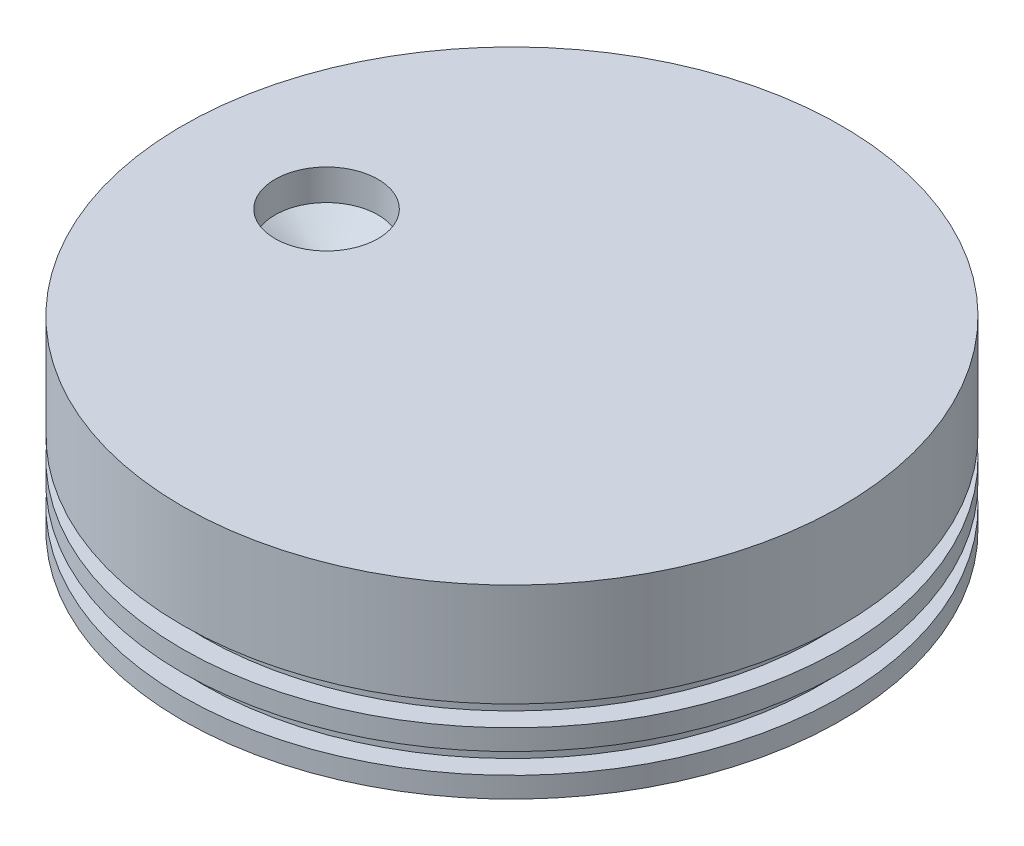
SolidWorks part; units mm, degrees
ref_plane "Front Plane" through (0, 0, 0) normal (0, 0, 1) x (1, 0, 0)
ref_plane "Top Plane" through (0, 0, 0) normal (0, 1, 0) x (1, 0, 0)
ref_plane "Right Plane" through (0, 0, 0) normal (1, 0, 0) x (0, 0, -1)
sketch "Sketch2" plane through (0, 0, 0) normal (0, 0, 1) x (1, 0, 0)
  line L0 (20.32, 0) -> (20.32, -11.43)
  line L1 (20.32, -11.43) -> (0, -11.43)
  line L2 (0, -11.43) -> (0, -10.16)
  line L3 (0, 0) -> (20.32, 0)
  line L4 (20.32, 0) -> (20.32, -34.3325) construction
  line L5 (0, -10.16) -> (1.27, -10.16)
  line L6 (1.27, -10.16) -> (1.27, -8.89)
  line L7 (1.27, -8.89) -> (0, -8.89)
  line L8 (0, -8.89) -> (0, -7.62)
  line L9 (0, -7.62) -> (1.27, -7.62)
  line L10 (1.27, -7.62) -> (1.27, -6.35)
  line L11 (1.27, -6.35) -> (0, -6.35)
  line L12 (0, -6.35) -> (0, 0)
  dimension "D1" = 20.32
  dimension "D2" = 1.27
  dimension "D3" = 1.27
  dimension "D4" = 1.27
  dimension "D5" = 6.35
  dimension "D6" = 1.27
  dimension "D7" = 11.43
revolve "base_revolve" add sketch "Sketch2" angle 360 about L4
sketch "Sketch5" plane through (0, 0, 0) normal (0, 1, 0) x (1, 0, 0)
  line L0 (0, 0) -> (8.89, 0) construction
  point P4 (8.89, 0)
  dimension "D1" = 8.89
hole_wizard "1/4 (0.25) Diameter Hole6" positions "Sketch5" profile "Sketch6" hole size "1/4" standard "ANSI Inch"
sketch "Sketch6" plane through (8.89, 0, 0) normal (1, 0, 0) x (0, 0, 1)
  line L0 (0, 0) -> (0, 3.81)
  line L1 (0, 3.81) -> (3.175, 1.9023)
  line L2 (3.175, 1.9023) -> (3.175, 0)
  line L5 (3.175, 0) -> (0, 0)
  line L10 (0, 3.81) -> (-3.175, 1.9023) construction
  line L11 (0, -6.35) -> (0, 107.95) construction
  dimension "Hole Dia." = 6.35
  dimension "Hole Depth" = 3.81
  dimension "Drill Angle" = 118
